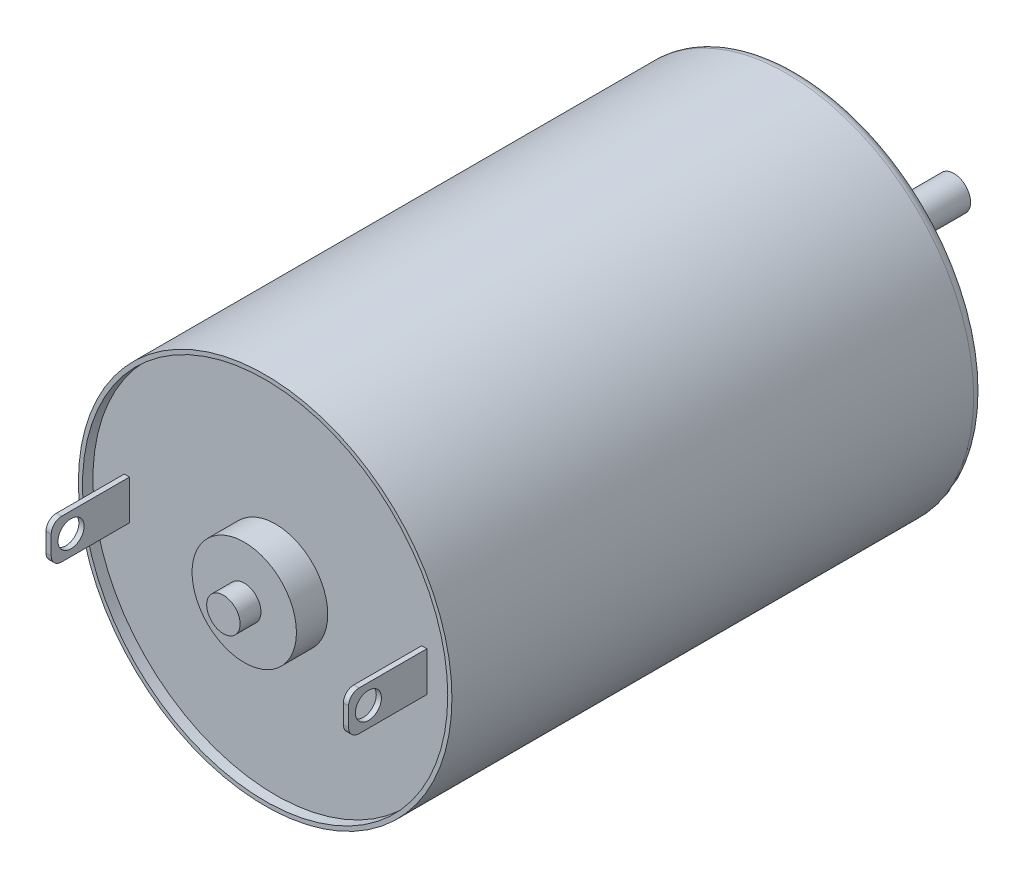
SolidWorks part; units mm, degrees
ref_plane "Front Plane" through (0, 0, 0) normal (0, 0, 1) x (1, 0, 0)
ref_plane "Top Plane" through (0, 0, 0) normal (0, 1, 0) x (1, 0, 0)
ref_plane "Right Plane" through (0, 0, 0) normal (1, 0, 0) x (0, 0, -1)
sketch "Sketch1" plane through (0, 0, 0) normal (0, 0, 1) x (1, 0, 0)
  circle A0 centre (0, 0) radius 17.9
  dimension "D1" = 35.8
extrude "Boss-Extrude1" add sketch "Sketch1" along normal blind 50
sketch "Sketch2" plane through (0, 0, 0) normal (0, 0, -1) x (-1, 0, 0)
  circle A0 centre (0, 0) radius 6.5
  dimension "D1" = 13
extrude "Boss-Extrude2" add sketch "Sketch2" along normal blind 4
sketch "Sketch4" plane through (0, 0, 50) normal (0, 0, 1) x (1, 0, 0)
  circle A0 centre (0, 0) radius 5
  dimension "D1" = 10
extrude "Boss-Extrude3" add sketch "Sketch4" along normal blind 3
sketch "Sketch3" plane through (0, 0, -4) normal (0, 0, -1) x (-1, 0, 0)
  circle A0 centre (0, 0) radius 1.6
  dimension "D1" = 3.2
extrude "Boss-Extrude4" add sketch "Sketch3" along normal blind 11 and the other way offset from surface (59 mm away) 2 other way up to face at (5, 0, 53)
sketch "Sketch5" plane through (0, 0, 50) normal (0, 0, 1) x (1, 0, 0)
  circle A0 centre (0, 0) radius 17.9 construction
  circle A1 centre (0, 0) radius 17.9
  circle A2 centre (0, 0) radius 17.5
  dimension "D1" = 0.4
extrude "Boss-Extrude5" add sketch "Sketch5" along normal blind 1
sketch "Sketch6" plane through (0, 0, 50) normal (0, 0, 1) x (1, 0, 0)
  line L0 (-14.25, 0) -> (0, 0) construction
  line L1 (-14.5, 1.9) -> (-14, 1.9)
  line L2 (-14.5, 1.9) -> (-14.5, -1.9)
  line L3 (-14.5, -1.9) -> (-14, -1.9)
  line L4 (-14, 1.9) -> (-14, -1.9)
  line L5 (-14.5, 1.9) -> (-14, -1.9) construction
  line L6 (-14.5, -1.9) -> (-14, 1.9) construction
  point P0 (-14.25, 0)
  dimension "D1" = 14.25
  dimension "D2" = 0.5
  dimension "D3" = 3.8
extrude "Boss-Extrude6" add sketch "Sketch6" along normal blind 7.5
sketch "Sketch7" plane through (-14.5, 0, 0) normal (-1, 0, 0) x (0, 0, 1)
  line L0 (55.6, 0) -> (55.6, 1.9) construction
  line L1 (57.5, 1.9) -> (50, 1.9) construction
  line L2 (55.6, 0) -> (57.5, 0) construction
  line L3 (57.5, 1.9) -> (57.5, -1.9) construction
  circle A0 centre (55.6, 0) radius 1.25
  dimension "D1" = 2.5
extrude "Cut-Extrude1" cut sketch "Sketch7" against normal up to surface (0.5 mm away) up to face at (-14, 0, 53.75)
fillet "Fillet1" radius 1 2 edges at (-14.25, 1.9, 57.5) (-14.25, -1.9, 57.5)
mirror "Mirror3" about plane through (0, 0, 0) normal (1, 0, 0) of "Fillet1", "Cut-Extrude1", "Boss-Extrude6"
fillet "Fillet2" radius 1 1 edges at (17.9, 0, 0)
fillet "Fillet3" radius 1 1 edges at (-6.5, 0, -4)
hole_wizard "M2.5x0.45 Tapped Hole1" positions "Sketch8" profile "Sketch9" tap size "M2.5x0.45" standard "ANSI Metric"
sketch "Sketch8" plane through (0, 0, 0) normal (0, 0, -1) x (-1, 0, 0)
  line L0 (-12.5, 0) -> (0, 0) construction
  line L1 (0, 0) -> (12.5, 0) construction
  point P0 (-12.5, 0)
  point P2 (12.5, 0)
  dimension "D1" = 25
sketch "Sketch9" plane through (12.5, 0, 0) normal (1, 0, 0) x (0, 1, 0)
  line L0 (0, 0) -> (0, 6.9659)
  line L1 (0, 6.9659) -> (1.025, 6.35)
  line L2 (1.025, 6.35) -> (1.025, 0)
  line L5 (1.025, 0) -> (0, 0)
  line L10 (0, 6.9659) -> (-1.025, 6.35) construction
  line L11 (0, -6.35) -> (0, 107.95) construction
  dimension "Tap Drill Dia." = 2.05
  dimension "Tap Drill Depth" = 6.35
  dimension "Drill Angle" = 118
cosmetic thread "Hole Thread1" parameters "D1"=5, "D2"=2.5
cosmetic thread "Hole Thread2" parameters "D1"=5, "D2"=2.5
